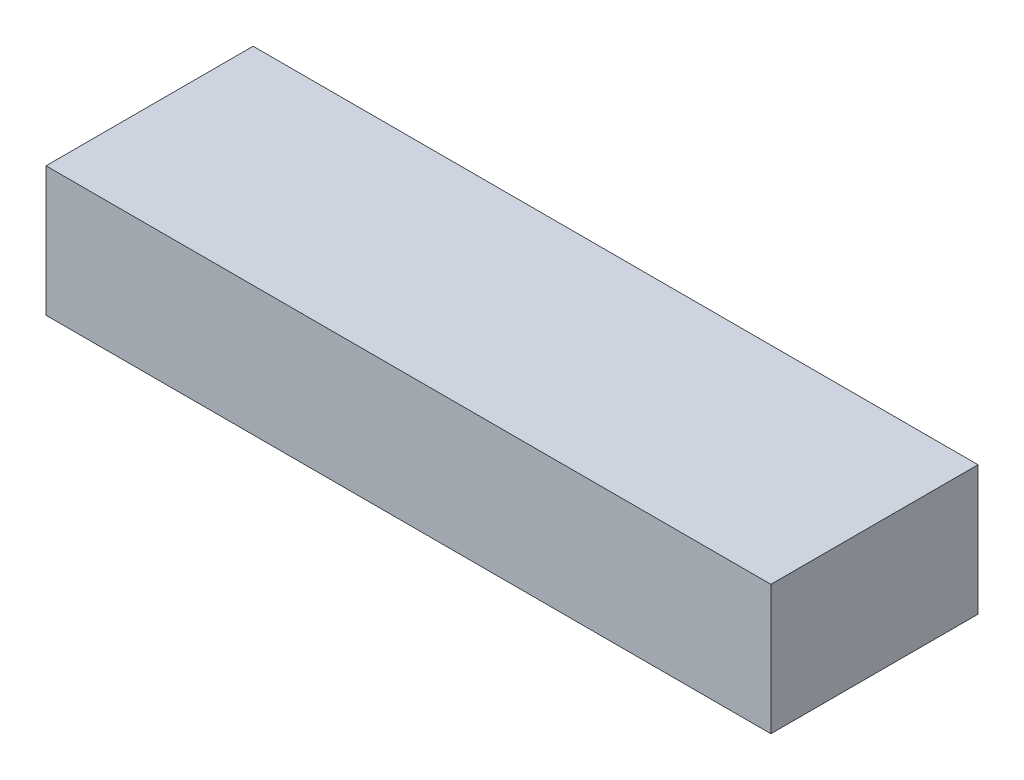
SolidWorks part; units mm, degrees
ref_plane "前视基准面" through (0, 0, 0) normal (0, 0, 1) x (1, 0, 0)
ref_plane "上视基准面" through (0, 0, 0) normal (0, 1, 0) x (1, 0, 0)
ref_plane "右视基准面" through (0, 0, 0) normal (1, 0, 0) x (0, 0, -1)
sketch "Sketch1" plane through (0, 0, 0) normal (1, 0, 0) x (0, 0, -1)
  line L1 (-20, 12.5) -> (20, 12.5)
  line L2 (-20, 12.5) -> (-20, -12.5)
  line L3 (-20, -12.5) -> (20, -12.5)
  line L4 (20, 12.5) -> (20, -12.5)
  line L5 (-20, 12.5) -> (20, -12.5) construction
  line L6 (-20, -12.5) -> (20, 12.5) construction
  point P0 (0, 0)
  dimension "D1" = 25
  dimension "D2" = 40
extrude "Boss-Extrude1" add sketch "Sketch1" along normal mid plane 140
